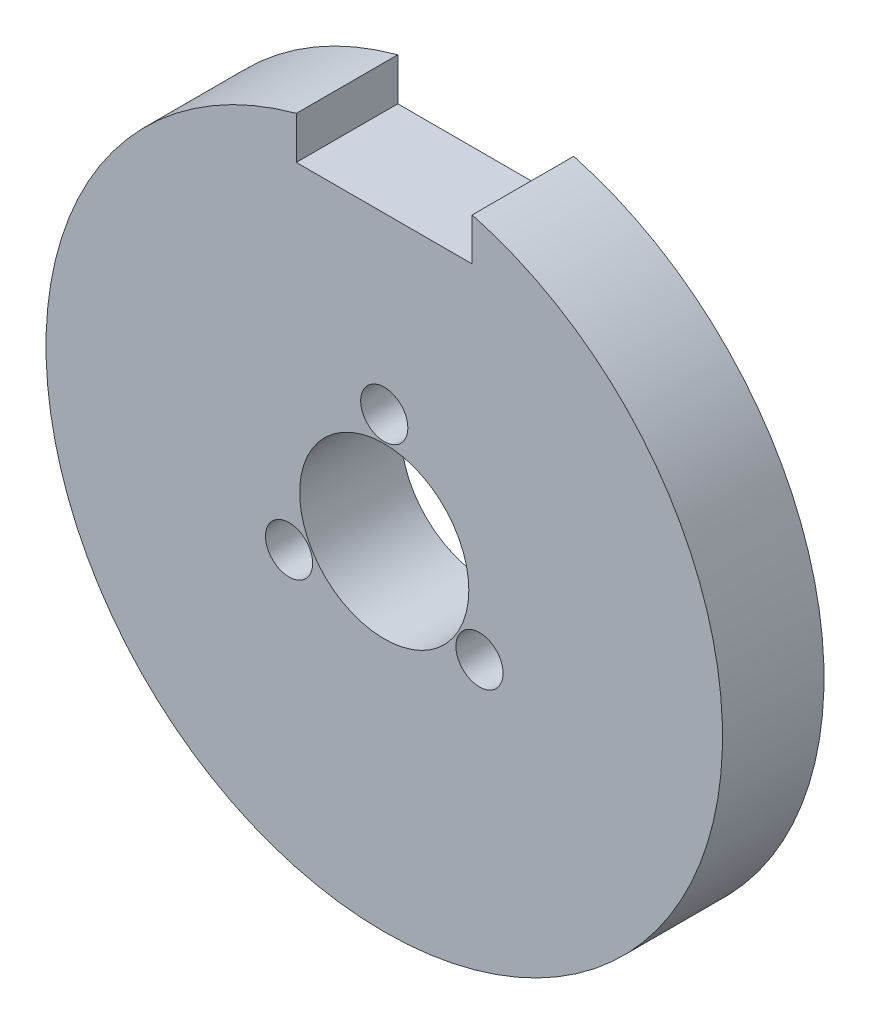
SolidWorks part; units mm, degrees
ref_plane "Plan de face" through (0, 0, 0) normal (0, 0, 1) x (1, 0, 0)
ref_plane "Plan de dessus" through (0, 0, 0) normal (0, 1, 0) x (1, 0, 0)
ref_plane "Plan de droite" through (0, 0, 0) normal (1, 0, 0) x (0, 0, -1)
sketch "Esquisse1" plane through (0, 0, 0) normal (0, 0, 1) x (1, 0, 0)
  circle A0 centre (0, 0) radius 20
  dimension "D1" = 40
extrude "Boss.-Extru.1" add sketch "Esquisse1" along normal blind 6
sketch "Esquisse2" plane through (0, 0, 6) normal (0, 0, 1) x (1, 0, 0)
  circle A0 centre (0, 0) radius 5
  dimension "D1" = 10
extrude "Enlèv. mat.-Extru.1" cut sketch "Esquisse2" against normal through all
sketch "Esquisse3" plane through (0, 0, 6) normal (0, 0, 1) x (1, 0, 0)
  line L0 (0, 13.7312) -> (0, -14.4163) construction
  line L1 (11.8916, -6.8656) -> (-12.4849, 7.2082) construction
  line L2 (-11.8916, -6.8656) -> (12.4849, 7.2082) construction
  circle A0 centre (0, 6.5) radius 1.3939
  circle A1 centre (5.6292, -3.25) radius 1.3939
  circle A2 centre (-5.6292, -3.25) radius 1.3939
  point P16 (0, 0)
  dimension "D1" = 6.5
  dimension "D2" = 3
extrude "Enlèv. mat.-Extru.2" cut sketch "Esquisse3" against normal through all
sketch "Esquisse4" plane through (0, 0, 0) normal (0, 0, -1) x (-1, 0, 0)
  line L0 (5.2, 27) -> (5.2, 16.8)
  line L3 (5, 17) -> (-5, 17) construction
  line L4 (5, 27) -> (5, 17) construction
  line L6 (-5, 17) -> (-5, 27) construction
  line L7 (5.2, 16.8) -> (-5.2, 16.8)
  line L8 (-5.2, 16.8) -> (-5.2, 27)
  line L9 (-5.2, 27) -> (5.3684, 27)
  circle M6 centre (0, 0) radius 20
  dimension "D1" = 0.2
extrude "Enlèv. mat.-Extru.3" cut sketch "Esquisse4" against normal through all contours L8 L7 L0 M6
